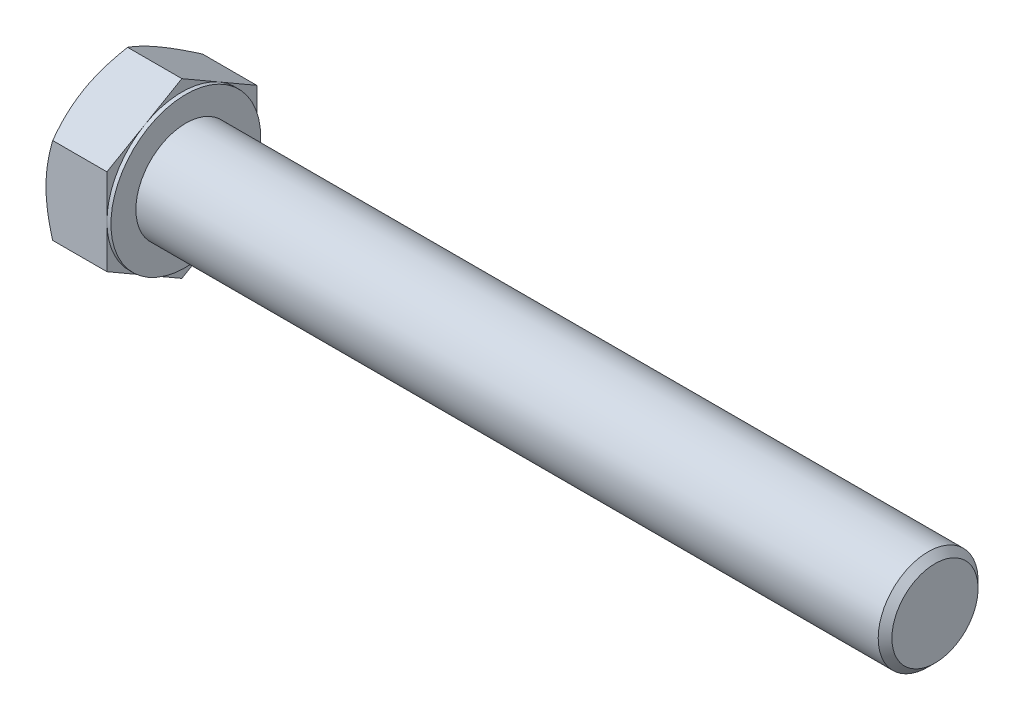
SolidWorks part; units mm, degrees
extrude "BaseHead" add sketch "HeadSke" along normal blind 13
sketch "HeadSke" plane through (0, 0, 0) normal (1, 0, 0) x (0, 0, -1)
  line L0 (15, 8.6603) -> (15, -8.6603)
  line L1 (-15, 8.6603) -> (-15, -8.6603)
  line L2 (15, -8.6603) -> (0, -17.3205)
  line L3 (0, -17.3205) -> (-15, -8.6603)
  line L4 (15, 8.6603) -> (0, 17.3205)
  line L5 (0, 17.3205) -> (-15, 8.6603)
  line L6 (0, 17.3205) -> (0, -17.3205) construction
  dimension "Width_flats" = 30
  dimension "D2" = 120
ref_plane "Plane1" through (0, 0, 0) normal (0, 0, 1) x (1, 0, 0)
ref_plane "Plane2" through (0, 0, 0) normal (0, 1, 0) x (1, 0, 0)
ref_plane "Plane3" through (0, 0, 0) normal (1, 0, 0) x (0, 0, -1)
sketch "BodySke" plane through (0, 0, 0) normal (0, 0, 1) x (1, 0, 0)
  line L0 (0, 8.6603) -> (0, -8.6603) construction
  line L1 (0, 0) -> (163, 0)
  line L2 (0, 0) -> (0, 10)
  line L3 (0, 10) -> (161.626, 10)
  line L4 (163, 0) -> (163, 8.626)
  line L5 (13, 17.3205) -> (13, 8.6603) construction
  line L6 (163, 8.626) -> (161.626, 10)
  line L7 (0, 0) -> (96.52, 0) construction
  line L8 (163, -8.626) -> (161.626, -10) construction
  line L9 (0, -10) -> (161.626, -10) construction
  line L10 (15.5, 15.24) -> (15.5, -1.27) construction
  line L11 (108, 6.8002) -> (108, -5.502) construction
  line L12 (13, 8.6603) -> (13, -8.6603) construction
  dimension "Thread_nom" = 55
  dimension "Diameter" = 20
  dimension "Advance" = 2.5
revolve "BaseBody" add sketch "BodySke"
cosmetic thread "ThreadCosmetic" [suppressed]
fillet "HeadFillet" [suppressed] radius 0.8
sketch "Sketch3" plane through (0, 0, 0) normal (0, 1, 0) x (1, 0, 0)
  line L0 (3.75, 21.4952) -> (-3.75, 8.5048)
  line L1 (3.75, 21.4952) -> (-8.3048, 28.455)
  line L2 (-3.75, 8.5048) -> (-15.8048, 15.4646)
  line L3 (-8.3048, 28.455) -> (-15.8048, 15.4646)
  line L4 (0, 15) -> (0, 0) construction
  line L6 (0, 0) -> (99.06, 0) construction
  dimension "D1" = 13.9196
  dimension "Head_ch_ang" = 30
revolve "HeadChamfer" cut sketch "Sketch3" angle 360 about L6
sketch "BearingSke" plane through (0, 0, 0) normal (0, 0, 1) x (1, 0, 0)
  line L0 (13, 17.3205) -> (1.3397, 17.3205) construction
  line L1 (13, 17.3205) -> (13, 8.6603) construction
  line L2 (13, 15) -> (12.2, 15)
  line L3 (13, 15) -> (13, 17.3205)
  line L4 (13, 17.3205) -> (12.2, 17.3205)
  line L5 (0, 0) -> (95.25, 0) construction
  line L6 (0, 0) -> (96.52, 0) construction
  line L7 (12.2, 15) -> (12.2, 17.3205)
  dimension "Bearing_ht" = 0.8
  dimension "Bearing_dia" = 30
revolve "BearingFace" cut sketch "BearingSke" angle 360 about L5
sketch "ThdSchSke" plane through (0, 0, 0) normal (0, 0, 1) x (1, 0, 0)
  line L0 (108, -8.626) -> (107.0379, -10)
  line L1 (108, -8.626) -> (108.9621, -10)
  line L2 (108.9621, -10) -> (108.9621, -12.5)
  line L3 (-3.175, 0) -> (5.1513, 0) construction
  line L5 (108.9621, -12.5) -> (107.0379, -12.5)
  line L6 (107.0379, -12.5) -> (107.0379, -10)
  dimension "Thread_minor" = 17.252
  dimension "Diameter" = 20
  dimension "Start" = 108
revolve "ThreadSchematic" [suppressed] cut sketch "ThdSchSke" angle 360 about L3
pattern_linear "ThdSchPat" [suppressed]
equation "\"Thread_minor@ThreadCosmetic\" = \"Minor_dia@BodySke\""
equation "\"Thread_length@ThreadCosmetic\" = ((sgn( (\"Length@BodySke\" - \"Advance@BodySke\" * 2.0 ) - \"Thread_nom@BodySke\" )-1)*( (\"Length@BodySke\" - \"Advance@BodySke\" * 2.0 ) - \"Thread_nom@BodySke\" ))/-2+ \"Thread_nom@BodySke\""
equation "\"Thread_minor@ThdSchSke\" = \"Minor_dia@BodySke\""
equation "\"Diameter@ThdSchSke\" = \"Diameter@BodySke\""
equation "\"Overcut@ThdSchSke\" = \"Diameter@BodySke\" * 1.25"
equation "\"Start@ThdSchSke\" = \"Head_ht@BaseHead\" + \"Length@BodySke\" - \"Thread_length@ThreadCosmetic\"  '---Non-countersunk---"
equation "\"Num_threads@ThdSchPat\" = int( \"Thread_length@ThreadCosmetic\" / \"Advance@BodySke\" + 0.999 )  + 1"
equation "\"Advance@ThdSchPat\" = \"Thread_length@ThreadCosmetic\" /  (\"Num_threads@ThdSchPat\" - 1) 'relax it"
equation "\"Num_threads@ThdSchPat\" = \"Num_threads@ThdSchPat\" - sgn( \"Num_threads@ThdSchPat\" - 1) '---chamfered tips only---"
